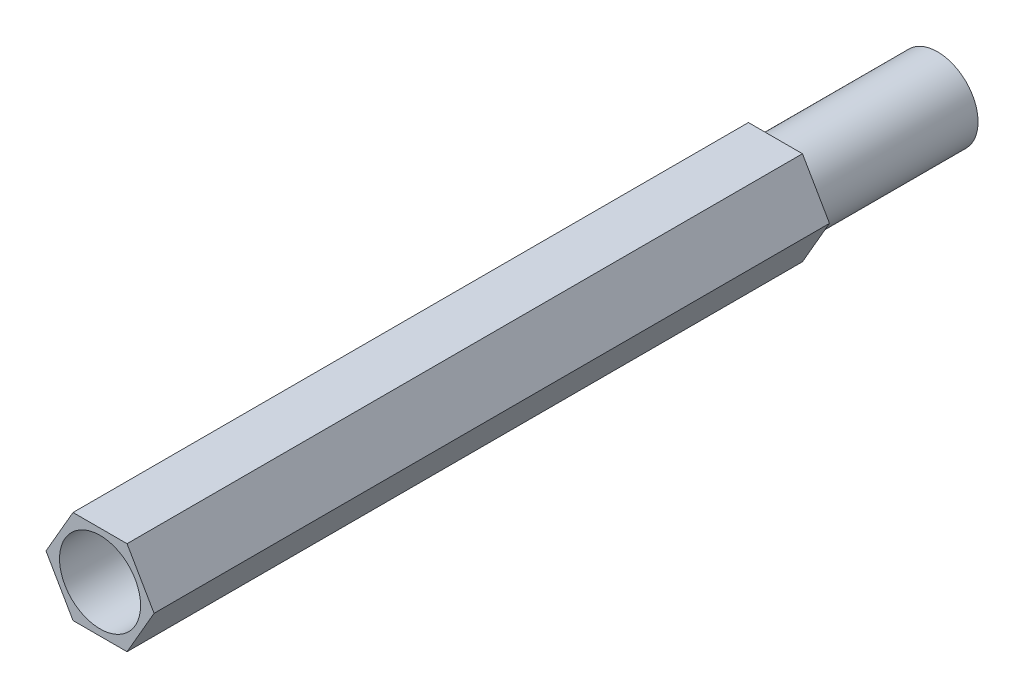
SolidWorks part; units mm, degrees
ref_plane "前视基准面" through (0, 0, 0) normal (0, 0, 1) x (1, 0, 0)
ref_plane "上视基准面" through (0, 0, 0) normal (0, 1, 0) x (1, 0, 0)
ref_plane "右视基准面" through (0, 0, 0) normal (1, 0, 0) x (0, 0, -1)
other "Configuration Table"
ref_plane "基准面1" through (0, 0, 0) normal (0, 0, -1) x (-1, 0, 0)
sketch "草图1" plane through (0, 0, 0) normal (0, 0, -1) x (-1, 0, 0)
  line L0 (1, -1.7321) -> (2, 0)
  line L1 (2, 0) -> (1, 1.7321)
  line L2 (1, 1.7321) -> (-1, 1.7321)
  line L3 (-1, 1.7321) -> (-2, 0)
  line L4 (-2, 0) -> (-1, -1.7321)
  line L5 (-1, -1.7321) -> (1, -1.7321)
  dimension "D1" = 1
  dimension "D2" = 3
  dimension "D3" = 4
  dimension "D4" = 1.7321
  dimension "D5" = 3.4641
extrude "凸台-拉伸1" add sketch "草图1" against normal blind 25
ref_plane "基准面2" through (0, 0, 0) normal (0, -1, 0) x (1, 0, 0)
sketch "草图2" plane through (0, 0, 0) normal (0, -1, 0) x (1, 0, 0)
  line L0 (1.5, 0) -> (0, 0)
  line L1 (0, 0) -> (0, -6)
  line L2 (0, -6) -> (1.5, -6)
  line L3 (1.5, -6) -> (1.5, 0)
  line L4 (0, 0) -> (0, -6) construction
  dimension "D1" = 1.5
  dimension "D2" = 6
revolve "旋转1" add sketch "草图2" angle 360 about L4
hole_wizard "Ø3.0 (3) 直径孔1" positions "草图4" profile "草图3" hole size "Ø3.0" standard "ANSI Metric"
sketch "草图4" plane through (0, 0, 25) normal (0, 0, 1) x (1, 0, 0)
  point P0 (0, 0)
sketch "草图3" plane through (0, 0, 25) normal (1, 0, 0) x (0, -1, 0)
  line L0 (0, 0) -> (0, 5)
  line L1 (0, 5) -> (1.5, 5)
  line L2 (1.5, 5) -> (1.5, 0)
  line L5 (1.5, 0) -> (0, 0)
  line L10 (0, 5) -> (-1.5, 5) construction
  line L11 (0, -6.35) -> (0, 107.95) construction
  dimension "孔直径" = 3
  dimension "孔深度" = 5
  dimension "导头角度" = 180
